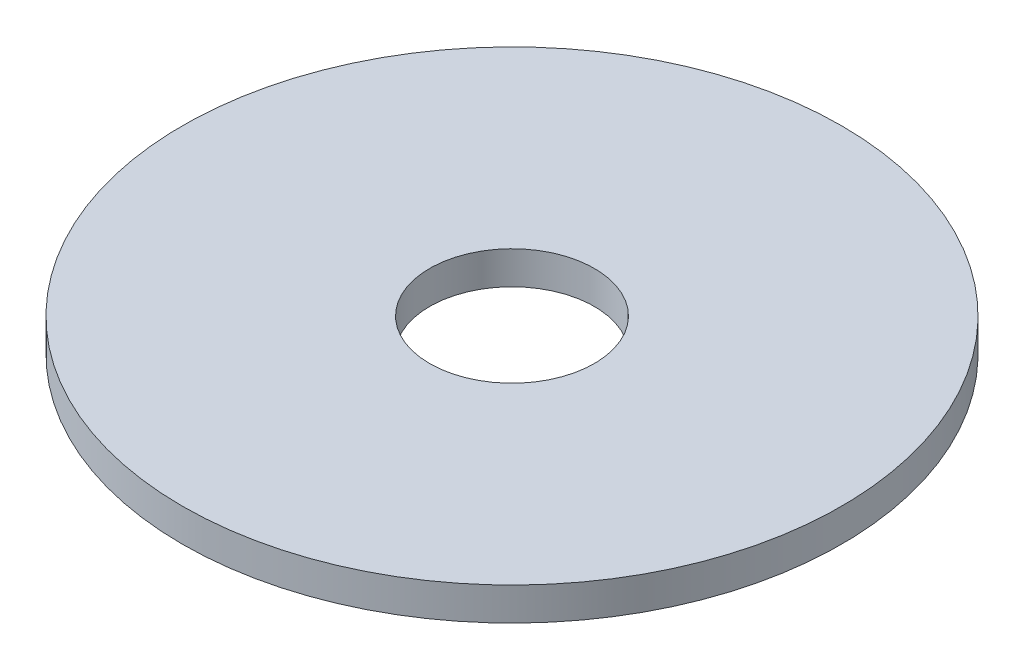
SolidWorks part; units mm, degrees
material "聚脂树脂"
ref_plane "前视基准面" through (0, 0, 0) normal (0, 0, 1) x (1, 0, 0)
ref_plane "上视基准面" through (0, 0, 0) normal (0, 1, 0) x (1, 0, 0)
ref_plane "右视基准面" through (0, 0, 0) normal (1, 0, 0) x (0, 0, -1)
other "Configuration Table"
sketch "草图1" plane through (0, 0, 0) normal (0, 1, 0) x (1, 0, 0)
  circle A0 centre (0, 0) radius 10
  circle A1 centre (0, 0) radius 2.5
  dimension "D1" = 5
  dimension "D2" = 20
extrude "凸台-拉伸1" add sketch "草图1" along normal blind 1
